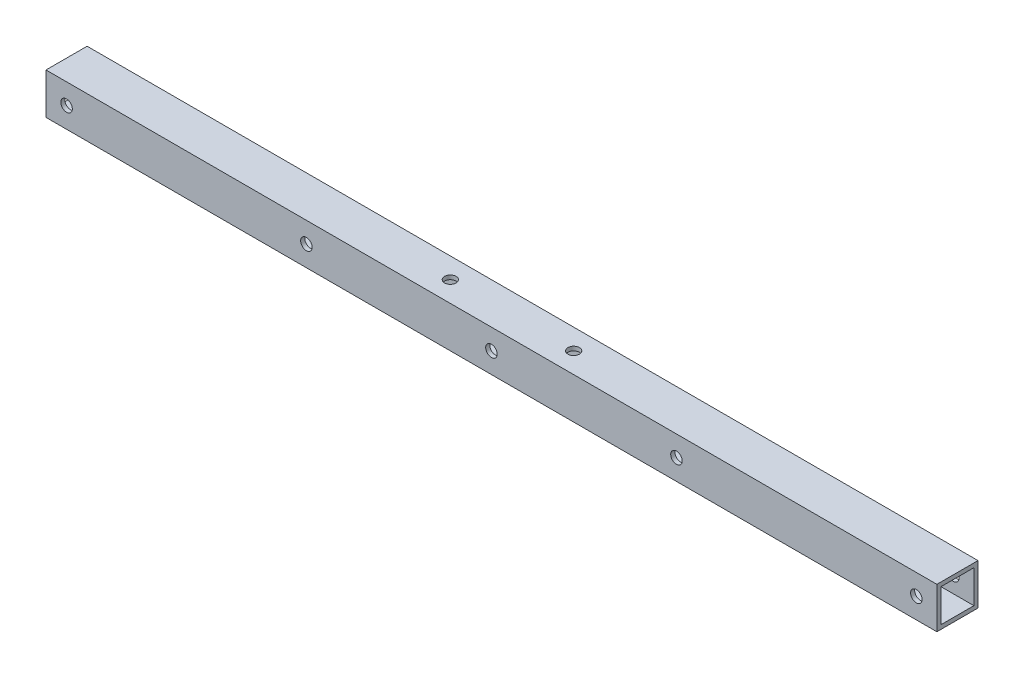
SolidWorks part; units mm, degrees
material "5052-H34"
ref_plane "正面" through (0, 0, 0) normal (0, 0, 1) x (1, 0, 0)
ref_plane "平面" through (0, 0, 0) normal (0, 1, 0) x (1, 0, 0)
ref_plane "右側面" through (0, 0, 0) normal (1, 0, 0) x (0, 0, -1)
sketch "ｽｹｯﾁ1" plane through (0, 0, 0) normal (1, 0, 0) x (0, 0, -1)
  line L1 (-7.5, 7.5) -> (7.5, 7.5)
  line L2 (-7.5, 7.5) -> (-7.5, -7.5)
  line L3 (-7.5, -7.5) -> (7.5, -7.5)
  line L4 (7.5, 7.5) -> (7.5, -7.5)
  line L5 (-7.5, 7.5) -> (7.5, -7.5) construction
  line L6 (-7.5, -7.5) -> (7.5, 7.5) construction
  point P0 (0, 0)
  dimension "D1" = 15
extrude "押し出し-薄板1" add sketch "ｽｹｯﾁ1" along normal blind 325 thin
sketch "ｽｹｯﾁ2" plane through (0, 0, 7.5) normal (0, 0, 1) x (1, 0, 0)
  line L0 (162.5, 7.5) -> (162.5, -7.5) construction
  line L1 (325, 7.5) -> (0, 7.5) construction
  line L2 (325, -7.5) -> (0, -7.5) construction
  line L3 (0, 0) -> (7.5, 0) construction
  circle A0 centre (7.5, 0) radius 2.1
  circle A1 centre (317.5, 0) radius 2.1
  dimension "D1" = 4.2
  dimension "D2" = 7.5
extrude "ｶｯﾄ - 押し出し1" cut sketch "ｽｹｯﾁ2" against normal through all
sketch "ｽｹｯﾁ3" plane through (0, 0, 7.5) normal (0, 0, 1) x (1, 0, 0)
  line L0 (162.5, 7.5) -> (162.5, -7.5) construction
  line L1 (325, 7.5) -> (0, 7.5) construction
  line L2 (325, -7.5) -> (0, -7.5) construction
  line L3 (162.5, 0) -> (95, 0) construction
  circle A0 centre (95, 0) radius 2.1
  circle A1 centre (230, 0) radius 2.1
  circle A2 centre (162.5, 0) radius 2.1
  dimension "D1" = 4.2
  dimension "D2" = 135
extrude "ｶｯﾄ - 押し出し2" cut sketch "ｽｹｯﾁ3" against normal through all
sketch "ｽｹｯﾁ4" plane through (0, 7.5, 0) normal (0, 1, 0) x (1, 0, 0)
  line L0 (162.5, 7.5) -> (162.5, -7.5) construction
  line L1 (325, 7.5) -> (0, 7.5) construction
  line L2 (325, -7.5) -> (0, -7.5) construction
  line L3 (162.5, 0) -> (140, 0) construction
  circle A0 centre (140, 0) radius 2.1
  circle A1 centre (185, 0) radius 2.1
  dimension "D1" = 4.2
  dimension "D2" = 45
extrude "ｶｯﾄ - 押し出し3" cut sketch "ｽｹｯﾁ4" against normal through all
